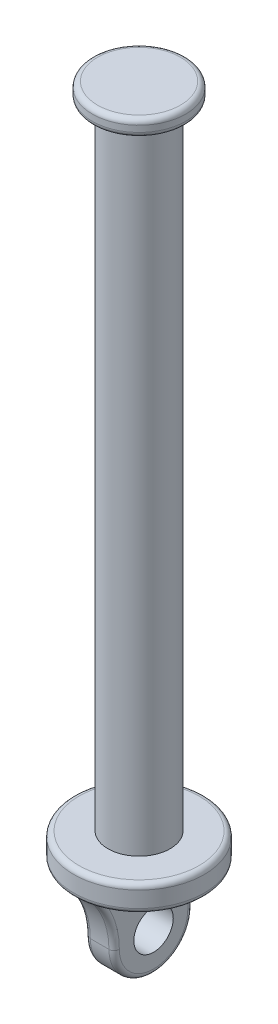
SolidWorks part; units mm, degrees
ref_plane "Front Plane" through (0, 0, 0) normal (0, 0, 1) x (1, 0, 0)
ref_plane "Top Plane" through (0, 0, 0) normal (0, 1, 0) x (1, 0, 0)
ref_plane "Right Plane" through (0, 0, 0) normal (1, 0, 0) x (0, 0, -1)
sketch "Sketch1" plane through (0, 0, 0) normal (0, 1, 0) x (1, 0, 0)
  circle A0 centre (0, 0) radius 15
  dimension "D1" = 30
extrude "Boss-Extrude1" add sketch "Sketch1" along normal blind 305
sketch "Sketch2" plane through (0, 305, 0) normal (0, 1, 0) x (1, 0, 0)
  circle A0 centre (0, 0) radius 22.5
  dimension "D1" = 45
extrude "Boss-Extrude2" add sketch "Sketch2" along normal blind 8
sketch "Sketch3" plane through (0, 0, 0) normal (0, -1, 0) x (1, 0, 0)
  circle A0 centre (0, 0) radius 31.5
  dimension "D1" = 63
extrude "Boss-Extrude3" add sketch "Sketch3" along normal blind 12.7
sketch "Sketch4" plane through (0, 0, 0) normal (1, 0, 0) x (0, 0, -1)
  line L0 (0, 0) -> (0, -92.9954) construction
  line L1 (-28.5, -12.7) -> (28.5, -12.7)
  arc A0 (-18.9999, -37.7449) -> (18.9999, -37.7449) centre (0, -37.7) ccw
  circle A1 centre (0, -37.7) radius 9.5
  arc A2 (28.5, -12.7) -> (18.9999, -37.7449) centre (56.9998, -37.8348) ccw
  arc A3 (-28.5, -12.7) -> (-18.9999, -37.7449) centre (-56.9998, -37.8348) cw
  point P4 (0, -12.7)
  dimension "D2" = 19
  dimension "D3" = 19
  dimension "D5" = 38
  dimension "D1" = 25
  dimension "D4" = 57
extrude "Boss-Extrude4" add sketch "Sketch4" along normal mid plane 14
fillet "Fillet3" radius 2.5 5 edges at (0, 305, 22.5) (0, 313, 22.5) (7, -24.3576, 21.4701) (7, -24.3576, -21.4701) (7, -56.7, 0)
fillet "Fillet4" radius 2.5 3 edges at (-7, -24.3576, 21.4701) (-7, -24.3576, -21.4701) (-7, -56.7, 0)
fillet "Fillet5" radius 2.5 2 edges at (0, 0, -31.5) (0, -12.7, -31.5)
